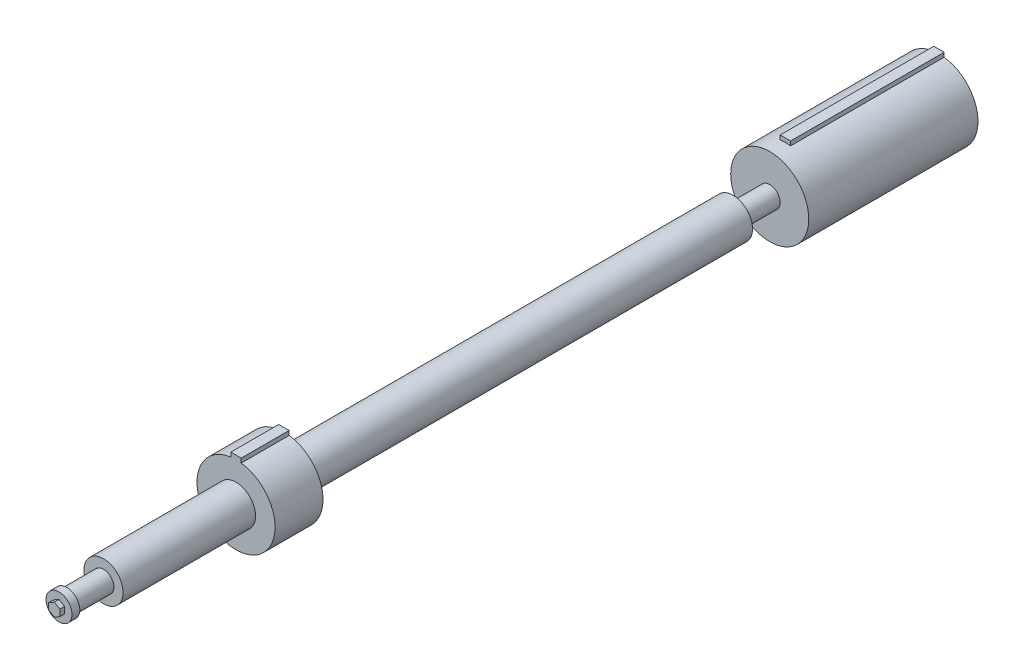
SolidWorks part; units mm, degrees
ref_plane "Alzado" through (0, 0, 0) normal (0, 0, 1) x (1, 0, 0)
ref_plane "Planta" through (0, 0, 0) normal (0, 1, 0) x (1, 0, 0)
ref_plane "Vista lateral" through (0, 0, 0) normal (1, 0, 0) x (0, 0, -1)
sketch "Croquis1" plane through (0, 0, 0) normal (0, 0, 1) x (1, 0, 0)
  circle A0 centre (0, 0) radius 4
  dimension "D1" = 8
extrude "Saliente-Extruir1" add sketch "Croquis1" along normal mid plane 270
sketch "Croquis2" plane through (0, 0, 135) normal (0, 0, 1) x (1, 0, 0)
  circle A0 centre (0, 0) radius 5
  dimension "D1" = 10
extrude "Saliente-Extruir2" add sketch "Croquis2" along normal blind 3
sketch "Croquis3" plane through (0, 0, 138) normal (0, 0, 1) x (1, 0, 0)
  line L1 (0, 2.5) -> (-2.1651, 1.25)
  line L2 (-2.1651, 1.25) -> (-2.1651, -1.25)
  line L3 (-2.1651, -1.25) -> (0, -2.5)
  line L4 (0, -2.5) -> (2.1651, -1.25)
  line L5 (2.1651, -1.25) -> (2.1651, 1.25)
  line L6 (2.1651, 1.25) -> (0, 2.5)
  circle A1 centre (0, 0) radius 2.1651 construction
extrude "Saliente-Extruir3" add sketch "Croquis3" along normal blind 1.8
sketch "Croquis4" plane through (0, 0, 0) normal (0, 0, 1) x (1, 0, 0)
  circle A0 centre (0, 0) radius 7.5
  dimension "D1" = 15
extrude "Saliente-Extruir4" add sketch "Croquis4" along normal mid plane 241.8
ref_plane "Plano1" through (0, 0, 70) normal (0, 0, -1) x (-1, 0, 0)
sketch "Croquis5" plane through (0, 0, 70) normal (0, 0, -1) x (-1, 0, 0)
  circle A0 centre (0, 0) radius 15
  dimension "D1" = 30
extrude "Saliente-Extruir5" add sketch "Croquis5" along normal blind 15
sketch "Croquis7" plane through (0, 0, 70) normal (0, 0, 1) x (1, 0, 0)
  line L0 (0, 7.5) -> (0, 15) construction
  line L2 (-2, 13.5) -> (2, 13.5)
  line L3 (-2, 13.5) -> (-2, 16.5)
  line L4 (-2, 16.5) -> (2, 16.5)
  line L5 (2, 13.5) -> (2, 16.5)
  line L6 (-2, 13.5) -> (2, 16.5) construction
  line L7 (-2, 16.5) -> (2, 13.5) construction
  circle A0 centre (0, 0) radius 7.5 construction
  circle A1 centre (0, 0) radius 15 construction
  dimension "D1" = 4
  dimension "D2" = 3
extrude "Saliente-Extruir6" add sketch "Croquis7" against normal up to surface (15 mm away) up to face at (-7.5, 0, 55)
sketch "Croquis8" plane through (0, 0, 55) normal (0, 0, -1) x (-1, 0, 0)
  line L3 (2, 14.8661) -> (2, 16.5)
  line L4 (2, 16.5) -> (-2, 16.5)
  line L5 (-2, 16.5) -> (-2, 14.8661)
  line L6 (2, 14.8661) -> (2, 16.5)
  line L7 (2, 16.5) -> (-2, 16.5)
  line L8 (-2, 16.5) -> (-2, 14.8661)
  arc A1 (-2, 14.8661) -> (2, 14.8661) centre (0, 0) ccw
  arc A2 (-2, 14.8661) -> (2, 14.8661) centre (0, 0) ccw
  dimension "D1" = 0
extrude "Saliente-Extruir7" add sketch "Croquis8" along normal blind 3.4
sketch "Croquis9" plane through (0, 0, -135) normal (0, 0, -1) x (-1, 0, 0)
  circle A0 centre (0, 0) radius 15
  dimension "D1" = 30
extrude "Saliente-Extruir8" add sketch "Croquis9" along normal blind 6
sketch "Croquis10" plane through (0, 0, -141) normal (0, 0, -1) x (-1, 0, 0)
  line L3 (-2, 14.8661) -> (-2, 16.5)
  line L4 (-2, 16.5) -> (2, 16.5)
  line L5 (2, 14.8661) -> (2, 16.5)
  arc A0 (-2, 14.8661) -> (2, 14.8661) centre (0, 0) ccw
  circle A1 centre (0, 0) radius 15
  arc A2 (-2, 14.8661) -> (2, 14.8661) centre (0, 0) ccw
  circle M2 centre (0, 0) radius 15
  dimension "D1" = 0
extrude "Saliente-Extruir9" add sketch "Croquis10" along normal blind 10 contours M2 | L5 L4 L3 M2
sketch "Croquis11" plane through (0, 0, -151) normal (0, 0, -1) x (-1, 0, 0)
  line L3 (2, 14.8661) -> (2, 16.5)
  line L4 (2, 16.5) -> (-2, 16.5)
  line L5 (-2, 16.5) -> (-2, 14.8661)
  line L6 (2, 14.8661) -> (2, 16.5)
  line L7 (2, 16.5) -> (-2, 16.5)
  line L8 (-2, 16.5) -> (-2, 14.8661)
  arc A1 (-2, 14.8661) -> (2, 14.8661) centre (0, 0) ccw
  arc A2 (-2, 14.8661) -> (2, 14.8661) centre (0, 0) ccw
  dimension "D1" = 0
extrude "Saliente-Extruir10" add sketch "Croquis11" along normal blind 49 contours A2 L6 L7 L8
